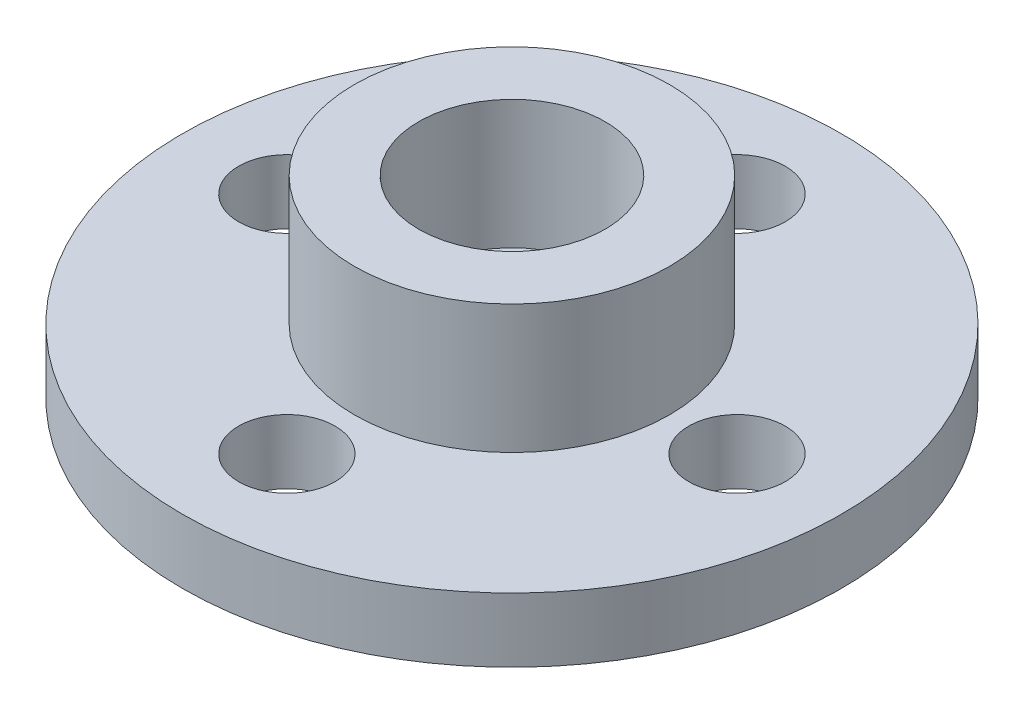
SolidWorks part; units mm, degrees
ref_plane "Front Plane" through (0, 0, 0) normal (0, 0, 1) x (1, 0, 0)
ref_plane "Top Plane" through (0, 0, 0) normal (0, 1, 0) x (1, 0, 0)
ref_plane "Right Plane" through (0, 0, 0) normal (1, 0, 0) x (0, 0, -1)
sketch "Sketch1" plane through (0, 0, 0) normal (0, 1, 0) x (1, 0, 0)
  circle A0 centre (0, 0) radius 10.25
  dimension "D1" = 20.5
extrude "Boss-Extrude1" add sketch "Sketch1" along normal blind 2
sketch "Sketch2" plane through (0, 2, 0) normal (0, 1, 0) x (1, 0, 0)
  line L0 (0, 0) -> (10.25, 0) construction
  line L1 (0, 0) -> (0, 10.25) construction
  line L2 (0, 0) -> (7.2478, 7.2478) construction
  line L3 (0, 0) -> (7.2478, -7.2478) construction
  circle A0 centre (0, 0) radius 10.25 construction
  circle A1 centre (7, 0) radius 1.5
  circle A2 centre (0, 0) radius 1.5
  circle A3 centre (0, 7) radius 1.5
  circle A4 centre (-7, 0) radius 1.5
  circle A5 centre (0, -7) radius 1.5
  dimension "D1" = 3
  dimension "D2" = 7
extrude "Cut-Extrude1" cut sketch "Sketch2" against normal blind 3
sketch "Sketch3" plane through (0, 2, 0) normal (0, 1, 0) x (1, 0, 0)
  circle A0 centre (0, 0) radius 2.9
  circle A1 centre (0, 0) radius 4.9
  dimension "D1" = 5.8
  dimension "D2" = 2
extrude "Boss-Extrude2" add sketch "Sketch3" along normal blind 4 contours A1 | A0
